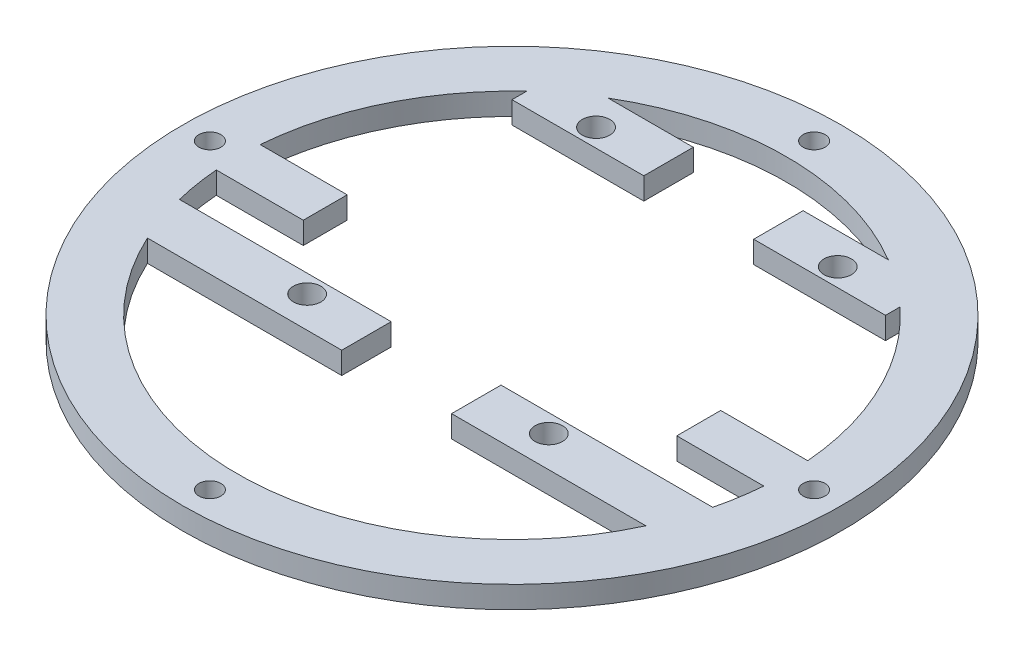
SolidWorks part; units mm, degrees
ref_plane "Front Plane" through (0, 0, 0) normal (0, 0, 1) x (1, 0, 0)
ref_plane "Top Plane" through (0, 0, 0) normal (0, 1, 0) x (1, 0, 0)
ref_plane "Right Plane" through (0, 0, 0) normal (1, 0, 0) x (0, 0, -1)
sketch "Sketch1" plane through (0, 0, 0) normal (0, 1, 0) x (1, 0, 0)
  circle A0 centre (0, 0) radius 30
  circle A1 centre (0, 0) radius 25
extrude "Boss-Extrude1" add sketch "Sketch1" along normal blind 2
sketch "Sketch2" plane through (0, 2, 0) normal (0, 1, 0) x (1, 0, 0)
  circle A1 centre (0, 27.5) radius 1
  circle A2 centre (27.5, 0) radius 1
  circle A3 centre (0, -27.5) radius 1
  circle A4 centre (-27.5, 0) radius 1
extrude "Cut-Extrude1" cut sketch "Sketch2" against normal through all contours A4 | A3 | A2 | A1
sketch "Sketch3" plane through (0, 0, 0) normal (0, 1, 0) x (1, 0, 0)
  line L2 (0, -2) -> (24.9199, -2)
  line L3 (24.9199, -2) -> (-24.9199, -2)
  line L4 (24.9199, 2) -> (-24.9199, 2)
  arc A0 (-24.9199, 2) -> (-24.9199, -2) centre (0, 0) ccw
  arc A1 (24.9199, -2) -> (24.9199, 2) centre (0, 0) ccw
extrude "Boss-Extrude2" add sketch "Sketch3" along normal blind 2 contours L2 A1 L4 A0 L3
sketch "Sketch13" plane through (0, 0, 0) normal (0, 1, 0) x (1, 0, 0)
  line L0 (17, 0) -> (17, 18.3303)
  line L1 (12.7574, 21.5) -> (5, 21.5)
  line L6 (5, 21.5) -> (5, -10.5)
  line L7 (5, -10.5) -> (17, -10.5)
  line L8 (17, -10.5) -> (17, 0)
  line L9 (-5, 0) -> (-5, 21.5)
  line L10 (-5, 21.5) -> (-12.7574, 21.5)
  line L11 (-17, 18.3303) -> (-17, -10.5)
  line L12 (-17, -10.5) -> (-5, -10.5)
  line L13 (-5, -10.5) -> (-5, 0)
  arc A0 (-12.7574, 21.5) -> (-17, 18.3303) centre (0, 0) ccw
  arc A1 (17, 18.3303) -> (12.7574, 21.5) centre (0, 0) ccw
extrude "Boss-Extrude3" add sketch "Sketch13" along normal blind 2
sketch "Sketch14" plane through (0, 2, 0) normal (0, 1, 0) x (1, 0, 0)
  line L0 (0, 0) -> (27.5, 0)
  line L1 (27.5, 0) -> (-27.5, 0)
  line L2 (17, 2) -> (17, -2)
  line L3 (5, 2) -> (5, -2)
  line L4 (-5, 2) -> (-5, -2)
  line L5 (-17, 2) -> (-17, -2)
  line L6 (5, 0) -> (5, 17)
  line L7 (5, 21.5) -> (5, 2) construction
  line L8 (5, 17) -> (17, 17)
  line L9 (17, 2) -> (17, 18.3303) construction
  line L10 (17, 17) -> (17, 0)
  line L11 (17, -2) -> (17, -12.3354)
  line L20 (17, 0) -> (17, -6)
  line L21 (17, -6) -> (5, -6)
  line L22 (5, -2) -> (5, -10.5) construction
  line L23 (5, -6) -> (5, 0)
  line L24 (5, -6) -> (-5, -6)
  line L25 (-5, -10.5) -> (-5, -2) construction
  line L26 (-5, -6) -> (-5, 17)
  line L27 (-5, 2) -> (-5, 21.5) construction
  line L28 (-5, 17) -> (-17, 17)
  line L29 (-17, 18.3303) -> (-17, 2) construction
  line L30 (-17, 17) -> (-17, -6)
  line L31 (-17, -2) -> (-17, -10.5) construction
  line L32 (-17, -6) -> (-5, -6)
  line L33 (-5, 2) -> (5, 2)
  line L34 (-5, -2) -> (5, -2)
  line M2 (-17, 18.3303) -> (-17, 2)
  line M5 (5, 2) -> (-5, 2)
  line M6 (-5, 2) -> (-5, 21.5)
  line M10 (5, 21.5) -> (5, 2)
  line M12 (-17, -2) -> (-17, -10.5)
  line M14 (-5, -10.5) -> (-5, -2)
  line M15 (-5, -2) -> (5, -2)
  line M16 (5, -2) -> (5, -10.5)
  line M22 (17, 2) -> (17, 18.3303)
extrude "Cut-Extrude2" cut sketch "Sketch14" against normal blind 2 contours L21 L11 L2 L1 L3 M16 | L8 L3 L1 L2 M10 M22 | L1 L4 L3 L0 M15 | L4 L1 L0 L3 M5 | L28 L5 L1 L4 M6 M2 | L32 L4 L1 L5 M12 M14
sketch "Sketch15" plane through (0, 0, 0) normal (0, 1, 0) x (1, 0, 0)
  line L0 (17, -6) -> (24.2693, -6)
  line L1 (17, -10.5) -> (22.6881, -10.5)
  line L2 (-17, -6) -> (-24.2693, -6)
  line L3 (-17, -10.5) -> (-22.6881, -10.5)
  line L4 (-17, -6) -> (-17, -10.5)
  line L5 (17, -6) -> (17, -10.5)
  arc A0 (-24.2693, -6) -> (-22.6881, -10.5) centre (0, 0) ccw
  arc A1 (22.6881, -10.5) -> (24.2693, -6) centre (0, 0) ccw
extrude "Boss-Extrude4" add sketch "Sketch15" along normal blind 2
sketch "Sketch16" plane through (0, 2, 0) normal (0, 1, 0) x (1, 0, 0)
  line L0 (0, 0) -> (11, 0)
  line L1 (0, 0) -> (-11, 0)
  line L2 (11, 0) -> (11, 18.65)
  line L3 (11, 0) -> (11, -7.65)
  line L4 (-11, 0) -> (-11, 18.65)
  line L5 (-11, 0) -> (-11, -7.65)
  circle A0 centre (11, 18.65) radius 1.25
  circle A1 centre (11, -7.65) radius 1.25
  circle A2 centre (-11, -7.65) radius 1.25
  circle A3 centre (-11, 18.65) radius 1.25
extrude "Cut-Extrude3" cut sketch "Sketch16" against normal blind 2 contours A0 | A1 | A2 | A3
